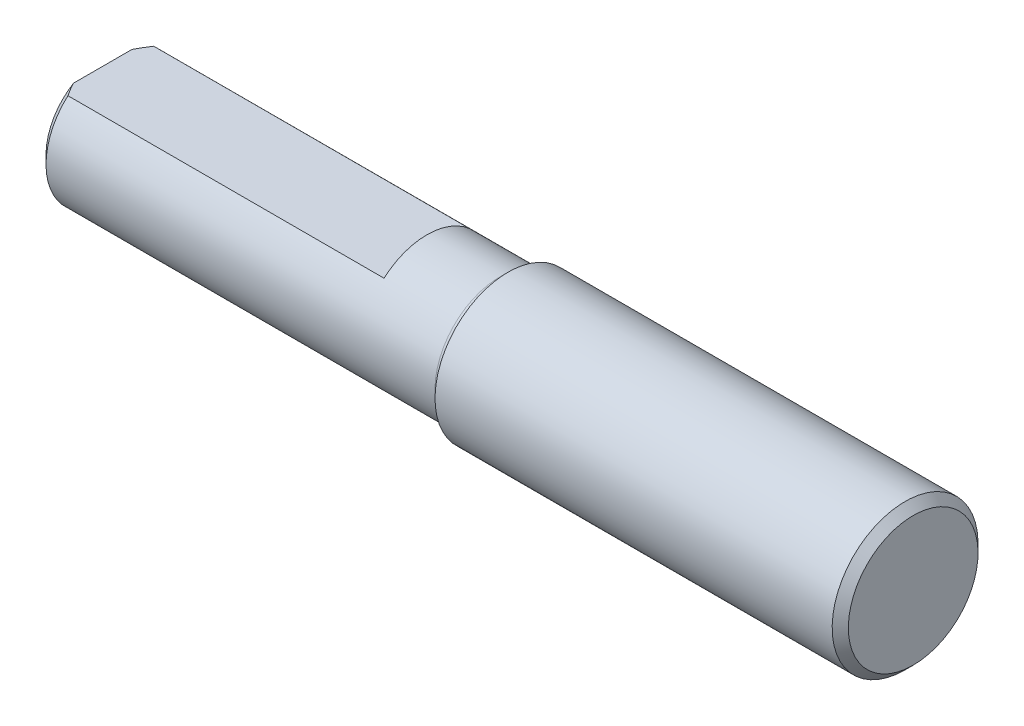
SolidWorks part; units mm, degrees
ref_plane "前视基准面" through (0, 0, 0) normal (0, 0, 1) x (1, 0, 0)
ref_plane "上视基准面" through (0, 0, 0) normal (0, 1, 0) x (1, 0, 0)
ref_plane "右视基准面" through (0, 0, 0) normal (1, 0, 0) x (0, 0, -1)
sketch "草图1" plane through (0, 0, 0) normal (0, 0, 1) x (1, 0, 0)
  line L3 (25, 0) -> (25, 4)
  line L5 (24.5, 4.5) -> (25, 4)
  line L7 (-24.5, 4) -> (-25, 3.5)
  line L10 (-24.5, 4) -> (-0.5, 4)
  line L11 (0, 4.5) -> (24.5, 4.5)
  line L21 (-25, 0) -> (25, 0)
  line L22 (-25, 0) -> (-25, 3.5)
  arc A0 (-0.5, 4) -> (0, 4.5) centre (-0.5, 4.5) ccw
revolve "旋转1" add sketch "草图1" angle 360 about L21
sketch "草图2" plane through (-25, 0, 0) normal (-1, 0, 0) x (0, 0, 1)
  line L0 (-2.6458, 3) -> (2.6458, 3)
  arc A0 (2.6458, 3) -> (-2.6458, 3) centre (0, 0) ccw
  dimension "D1" = 3
extrude "切除-拉伸1" cut sketch "草图2" against normal blind 20
